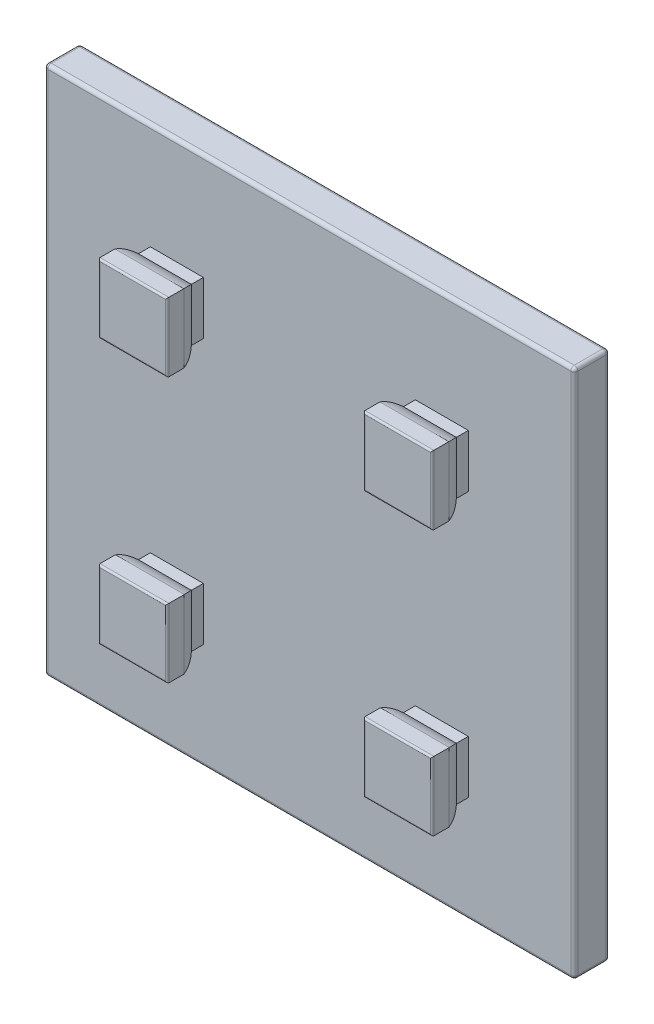
SolidWorks part; units mm, degrees
ref_plane "前视基准面" through (0, 0, 0) normal (0, 0, 1) x (1, 0, 0)
ref_plane "上视基准面" through (0, 0, 0) normal (0, 1, 0) x (1, 0, 0)
ref_plane "右视基准面" through (0, 0, 0) normal (1, 0, 0) x (0, 0, -1)
sketch "草图1" plane through (0, 0, 0) normal (0, 0, 1) x (1, 0, 0)
  line L1 (-15, -15) -> (15, -15)
  line L2 (-15, -15) -> (-15, 15)
  line L3 (-15, 15) -> (15, 15)
  line L4 (15, -15) -> (15, 15)
extrude "凸台-拉伸1" add sketch "草图1" against normal blind 2
sketch "草图2" plane through (0, 0, 0) normal (0, 0, 1) x (1, 0, 0)
  line L9 (-9, -9) -> (-6, -9)
  line L10 (-9, -9) -> (-9, -6)
  line L11 (-9, -6) -> (-6, -6)
  line L12 (-6, -9) -> (-6, -6)
  line L13 (6, -9) -> (9, -9)
  line L14 (6, -9) -> (6, -6)
  line L15 (6, -6) -> (9, -6)
  line L16 (9, -9) -> (9, -6)
extrude "凸台-拉伸2" add sketch "草图2" along normal blind 1
sketch "草图3" plane through (0, 0, 0) normal (0, -1, 0) x (1, 0, 0)
  line L0 (-9.45, 2.5) -> (-5.55, 2.5)
  line L1 (-9.45, 2.5) -> (-9.45, 1.5556)
  line L2 (-5.55, 2.5) -> (-5.55, 1.5556)
  line L3 (0, 3.1024) -> (0, -2.3254) construction
  line L4 (-9, 0.6771) -> (-6, 0.6771)
  line L5 (9, 0.6771) -> (6, 0.6771)
  line L6 (5.55, 2.5) -> (5.55, 1.5556)
  line L7 (9.45, 2.5) -> (9.45, 1.5556)
  line L8 (9.45, 2.5) -> (5.55, 2.5)
  arc A0 (6, 0.6771) -> (5.55, 1.5556) centre (7.5, 2) cw
  arc A1 (-9.45, 1.5556) -> (-9, 0.6771) centre (-7.5, 2) ccw
  arc A2 (9.45, 1.5556) -> (9, 0.6771) centre (7.5, 2) cw
  arc A3 (-6, 0.6771) -> (-5.55, 1.5556) centre (-7.5, 2) ccw
extrude "凸台-拉伸3" add sketch "草图3" along normal blind 5 from offset 5
sketch "草图4" plane through (-9.45, 0, 0) normal (-1, 0, 0) x (0, 0, 1)
  line L0 (2.5, -5.553) -> (1.5282, -5.5564)
  line L1 (0.6771, -10) -> (2.5, -10)
  line L2 (0.6771, -10) -> (0.6771, -9)
  line L3 (0.6771, -5) -> (2.5, -5)
  line L4 (2.5, -10) -> (2.5, -9.45)
  line L5 (2.5, -9.45) -> (1.5556, -9.45)
  line L6 (2.5, -5.553) -> (2.5, -5)
  line L7 (0.6771, -6) -> (0.6771, -5)
  arc A0 (0.6771, -9) -> (1.5556, -9.45) centre (2, -7.5) ccw
  arc A2 (1.5282, -5.5564) -> (0.6771, -6) centre (2, -7.5) ccw
extrude "切除-拉伸1" cut sketch "草图4" against normal through all
mirror "镜向1" about plane through (0, 0, 0) normal (0, 1, 0) of "凸台-拉伸2", "凸台-拉伸3", "切除-拉伸1"
fillet "圆角1" radius 0.1 16 edges at (7.5, 5.553, 2.5) (5.55, 7.5015, 2.5) (7.5, 9.45, 2.5) (9.45, 7.5015, 2.5) (7.5, -5.553, 2.5) (9.45, -7.5015, 2.5) (7.5, -9.45, 2.5) (5.55, -7.5015, 2.5) (-7.5, -5.553, 2.5) (-5.55, -7.5015, 2.5) (-7.5, -9.45, 2.5) (-9.45, -7.5015, 2.5) (-7.5, 5.553, 2.5) (-9.45, 7.5015, 2.5) (-7.5, 9.45, 2.5) (-5.55, 7.5015, 2.5)
fillet "圆角2" radius 0.2 12 edges at (0, -15, -2) (0, -15, 0) (-15, -15, -1) (-15, 0, -2) (-15, 0, 0) (-15, 15, -1) (0, 15, -2) (0, 15, 0) (15, 15, -1) (15, 0, -2) (15, -15, -1) (15, 0, 0)
